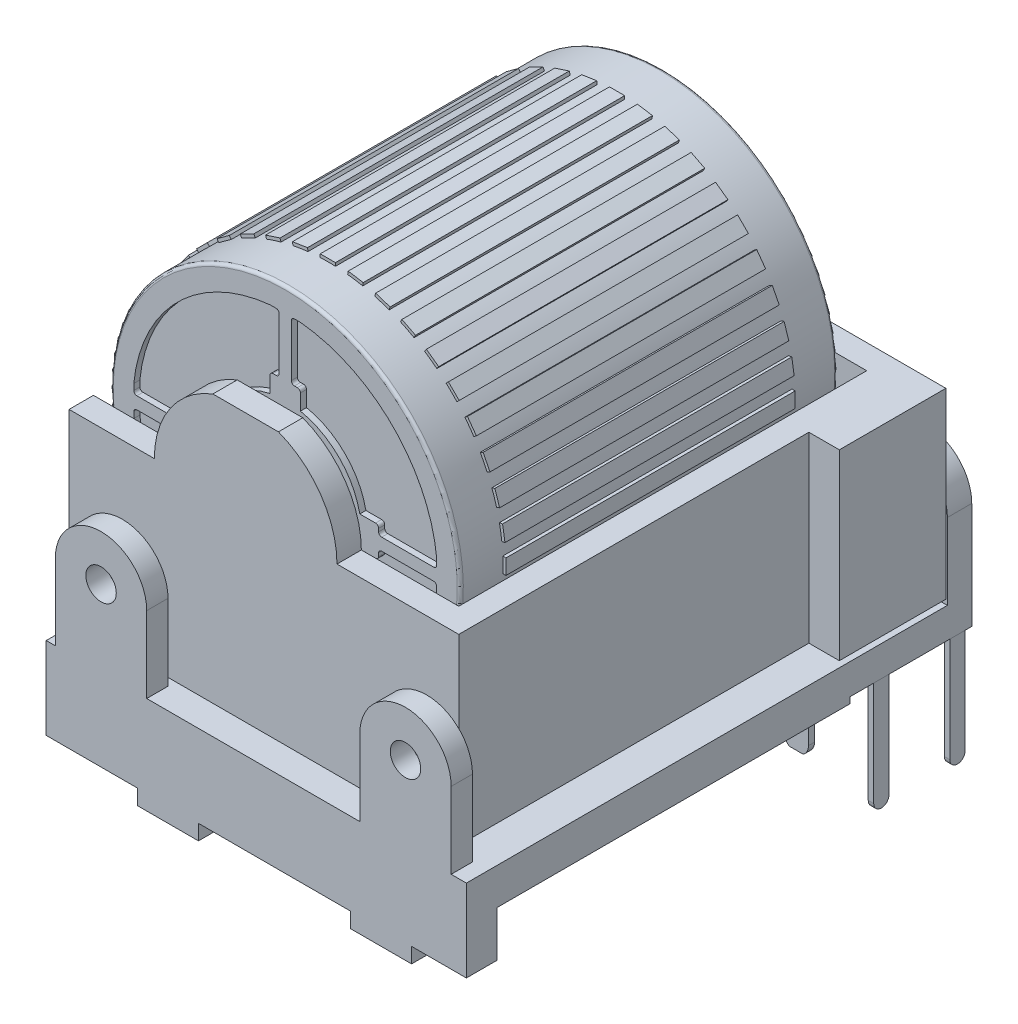
SolidWorks part; units mm, degrees
ref_plane "前视基准面" through (0, 0, 0) normal (0, 0, 1) x (1, 0, 0)
ref_plane "上视基准面" through (0, 0, 0) normal (0, 1, 0) x (1, 0, 0)
ref_plane "右视基准面" through (0, 0, 0) normal (1, 0, 0) x (0, 0, -1)
sketch "草图1" plane through (0, 0, 0) normal (0, 1, 0) x (1, 0, 0)
  line L0 (0, 0) -> (13.8, 0)
  line L1 (13.8, 0) -> (13.8, 16.6)
  line L2 (13.8, 16.6) -> (0, 16.6)
  line L3 (0, 16.6) -> (0, 0)
extrude "凸台-拉伸1" add sketch "草图1" along normal blind 1.2
sketch "草图2" plane through (0, 0, 0) normal (0, -1, 0) x (1, 0, 0)
  line L0 (0, 0) -> (13.8, 0)
  line L1 (13.8, 0) -> (13.8, -1)
  line L2 (13.8, 0) -> (13.8, -16.6) construction
  line L3 (13.8, -1) -> (0, -1)
  line L4 (0, -16.6) -> (0, 0) construction
  line L5 (0, -1) -> (0, 0)
extrude "凸台-拉伸2" add sketch "草图2" along normal blind 1.5
sketch "草图3" plane through (0, -1.5, 0) normal (0, -1, 0) x (1, 0, 0)
  line L1 (13.8, 0) -> (0, 0) construction
  line L2 (12, 0) -> (12, -2.2)
  line L4 (12, -2.2) -> (10, -2.2)
  line L5 (10, -2.2) -> (10, 0)
  line L6 (10, 0) -> (12, 0)
  line L7 (3, 0) -> (3, -2.2)
  line L8 (3, -2.2) -> (5, -2.2)
  line L9 (5, -2.2) -> (5, 0)
  line L10 (5, 0) -> (3, 0)
extrude "凸台-拉伸3" add sketch "草图3" along normal blind 0.5
sketch "草图4" plane through (0, 0, 0) normal (0, 0, 1) x (1, 0, 0)
  line L1 (0, 1.2) -> (13.8, 1.2) construction
  line L2 (0.3, 1.2) -> (0.3, 3.7)
  line L4 (3.3, 3.7) -> (3.3, 1.2)
  line L5 (3.3, 1.2) -> (0.3, 1.2)
  line L7 (13.3, 1.2) -> (13.3, 3.7)
  line L9 (10.3, 3.7) -> (10.3, 1.2)
  line L10 (10.3, 1.2) -> (13.3, 1.2)
  arc A0 (0.3, 3.7) -> (3.3, 3.7) centre (1.8, 3.7) cw
  arc A1 (10.3, 3.7) -> (13.3, 3.7) centre (11.8, 3.7) cw
  circle A2 centre (1.8, 3.7) radius 0.5
  circle A3 centre (11.8, 3.7) radius 0.5
extrude "凸台-拉伸4" add sketch "草图4" against normal blind 0.7
sketch "草图5" plane through (0, 0, -16.6) normal (0, 0, -1) x (-1, 0, 0)
  line L1 (-0.3, 1.2) -> (-3.3, 1.2) construction
  line L2 (-2, 1.2) -> (-2, 3.7)
  line L3 (-3.5, 5.2) -> (-12.3, 5.2)
  line L4 (-13.8, 3.7) -> (-13.8, 1.2)
  line L5 (-13.8, 1.2) -> (-2, 1.2)
  arc A0 (-2, 3.7) -> (-3.5, 5.2) centre (-3.5, 3.7) ccw
  arc A1 (-13.8, 3.7) -> (-12.3, 5.2) centre (-12.3, 3.7) cw
  circle A2 centre (-12.5, 3.7) radius 0.5
  circle A3 centre (-3.3, 3.7) radius 0.5
  dimension "D1" = 1.5
extrude "凸台-拉伸5" add sketch "草图5" against normal blind 0.8
sketch "草图6" plane through (0, 0, 0) normal (0, -1, 0) x (1, 0, 0)
  line L2 (11, -2.7) -> (12.5, -2.7)
  line L3 (12.5, -2.7) -> (12.5, -1)
  line L4 (12, -1) -> (13.8, -1) construction
  line L5 (12.5, -1) -> (9.5, -1)
  line L6 (5, -1) -> (10, -1) construction
  line L7 (9.5, -1) -> (9.5, -2.7)
  line L8 (9.5, -2.7) -> (11, -2.7)
  line L10 (4, -2.7) -> (5.5, -2.7)
  line L11 (5.5, -2.7) -> (5.5, -1)
  line L12 (5.5, -1) -> (2.5, -1)
  line L13 (0, -1) -> (13.8, -1) construction
  line L14 (2.5, -1) -> (2.5, -2.7)
  line L15 (2.5, -2.7) -> (4, -2.7)
extrude "切除-拉伸1" cut sketch "草图6" against normal through all
sketch "草图7" plane through (0, 0, 0) normal (0, -1, 0) x (1, 0, 0)
  line L0 (13.8, -16.6) -> (12.5, -16.6)
  line L2 (13.8, -16.6) -> (0, -16.6) construction
  line L3 (2, -14.8) -> (2, -11.3)
  line L4 (2, -11.3) -> (10, -11.3)
  line L5 (10, -11.3) -> (10, -12.3)
  line L6 (2, -14.8) -> (12, -14.8)
  line L7 (12, -14.8) -> (12, -12.3)
  line L8 (12, -12.3) -> (10, -12.3)
  line L9 (12.5, -16.6) -> (12.5, -12.6)
  line L10 (12.5, -12.6) -> (13.8, -12.6)
  line L11 (13.8, -1) -> (13.8, -16.6) construction
  line L12 (13.8, -12.6) -> (13.8, -16.6)
extrude "切除-拉伸2" cut sketch "草图7" against normal blind 0.2
sketch "草图8" plane through (0, 0.2, 0) normal (0, -1, 0) x (1, 0, 0)
  line L2 (2, -11.3) -> (2, -14.8) construction
  line L3 (2, -13.05) -> (12, -13.05)
  line L4 (12, -14.8) -> (12, -12.3) construction
  line L5 (12, -13.05) -> (12, -12.3)
  line L6 (12, -12.3) -> (10, -12.3) construction
  line L7 (12, -12.3) -> (10, -12.3) construction
  line L8 (12, -12.3) -> (10, -12.3)
  line L9 (10, -12.3) -> (10, -11.3)
  line L10 (10, -11.3) -> (2, -11.3)
  line L11 (2, -11.3) -> (2, -13.05)
extrude "切除-拉伸3" cut sketch "草图8" against normal through all
sketch "草图9" plane through (0, 0.2, 0) normal (0, -1, 0) x (1, 0, 0)
  line L2 (10.81, -14.025) -> (11.21, -14.025)
  line L4 (11.21, -14.025) -> (11.21, -13.825)
  line L6 (13.78, -16.4) -> (13.6, -16.4)
  line L7 (13.6, -16.4) -> (13.6, -15.9)
  line L8 (13.6, -15.9) -> (13.78, -15.9)
  line L9 (11.21, -13.825) -> (10.41, -13.825)
  line L10 (10.41, -13.825) -> (10.41, -14.025)
  line L11 (10.41, -14.025) -> (10.81, -14.025)
  line L13 (8.27, -14.025) -> (8.67, -14.025)
  line L14 (8.67, -14.025) -> (8.67, -13.825)
  line L15 (8.67, -13.825) -> (7.87, -13.825)
  line L16 (7.87, -13.825) -> (7.87, -14.025)
  line L17 (7.87, -14.025) -> (8.27, -14.025)
  line L18 (13.78, -16.4) -> (13.78, -15.9)
  line L19 (5.73, -14.025) -> (6.13, -14.025)
  line L20 (6.13, -14.025) -> (6.13, -13.825)
  line L21 (6.13, -13.825) -> (5.33, -13.825)
  line L22 (5.33, -13.825) -> (5.33, -14.025)
  line L23 (5.33, -14.025) -> (5.73, -14.025)
  line L24 (13.78, -13.9) -> (13.6, -13.9)
  line L25 (3.19, -14.025) -> (3.59, -14.025)
  line L26 (3.59, -14.025) -> (3.59, -13.825)
  line L27 (3.59, -13.825) -> (2.79, -13.825)
  line L28 (2.79, -13.825) -> (2.79, -14.025)
  line L29 (2.79, -14.025) -> (3.19, -14.025)
  line L30 (13.6, -13.9) -> (13.6, -13.4)
  line L31 (13.6, -13.4) -> (13.78, -13.4)
  line L33 (13.78, -13.9) -> (13.78, -13.4)
extrude "凸台-拉伸6" add sketch "草图9" along normal blind 3.7
sketch "草图11" plane through (13.78, 0, 0) normal (1, 0, 0) x (0, 0, -1)
  line L1 (13.9, -3.5) -> (13.4, -3.5) construction
  line L3 (16.4, -3.5) -> (15.9, -3.5) construction
  line L5 (15.9, -3.5) -> (15.9, 0.2) construction
  line L6 (15.9, -3.25) -> (15.9, -3.5)
  line L7 (15.9, -3.5) -> (16.15, -3.5)
  line L8 (16.15, -3.5) -> (16.4, -3.5)
  line L9 (16.4, -3.5) -> (16.4, -3.25)
  line L10 (16.4, -3.5) -> (16.4, 0.2) construction
  line L11 (13.4, -3.25) -> (13.4, -3.5)
  line L12 (13.4, -3.5) -> (13.4, 0.2) construction
  line L13 (13.4, -3.5) -> (13.9, -3.5)
  line L14 (13.9, -3.5) -> (13.9, -3.25)
  line L15 (13.9, -3.5) -> (13.9, 0.2) construction
  arc A0 (13.4, -3.25) -> (13.65, -3.5) centre (13.65, -3.25) ccw
  arc A1 (13.65, -3.5) -> (13.9, -3.25) centre (13.65, -3.25) ccw
  arc A2 (15.9, -3.25) -> (16.4, -3.25) centre (16.15, -3.25) ccw
  line M6 (13.4, 0.2) -> (13.4, -3.5)
  line M7 (13.4, -3.5) -> (13.9, -3.5)
  line M8 (13.9, -3.5) -> (13.9, 0.2)
extrude "切除-拉伸5" cut sketch "草图11" against normal blind 3.7 contours A0 M6 M7 | A1 L13 M8 | A2 L6 L7 | A2 L8 L9
sketch "草图10" plane through (0, 0, -14.025) normal (0, 0, -1) x (-1, 0, 0)
  line L22 (-8.67, -3.5) -> (-8.67, 0.2) construction
  line L23 (-10.41, -3.5) -> (-11.21, -3.5) construction
  line L25 (-7.87, -3.5) -> (-8.67, -3.5) construction
  line L26 (-11.21, -3.5) -> (-11.21, 0.2) construction
  line L27 (-10.41, -3.5) -> (-10.41, 0.2) construction
  line L28 (-11.21, -3.1) -> (-11.21, -3.5)
  line L29 (-11.21, -3.5) -> (-10.81, -3.5)
  line L30 (-10.81, -3.5) -> (-10.41, -3.5)
  line L31 (-10.41, -3.5) -> (-10.41, -3.1)
  line L32 (-7.87, -3.5) -> (-7.87, 0.2) construction
  line L33 (-6.13, -3.5) -> (-6.13, 0.2) construction
  line L34 (-5.33, -3.5) -> (-5.33, 0.2) construction
  line L35 (-3.59, -3.5) -> (-3.59, 0.2) construction
  line L36 (-2.79, -3.5) -> (-2.79, 0.2) construction
  line L37 (-8.67, -3.1) -> (-8.67, -3.5)
  line L38 (-8.67, -3.5) -> (-8.27, -3.5)
  line L39 (-8.27, -3.5) -> (-7.87, -3.5)
  line L40 (-7.87, -3.5) -> (-7.87, -3.1)
  line L41 (-6.13, -3.1) -> (-6.13, -3.5)
  line L42 (-6.13, -3.5) -> (-5.73, -3.5)
  line L43 (-5.73, -3.5) -> (-5.33, -3.5)
  line L44 (-5.33, -3.5) -> (-5.33, -3.1)
  line L45 (-3.59, -3.1) -> (-3.59, -3.5)
  line L46 (-3.59, -3.5) -> (-3.19, -3.5)
  line L47 (-3.19, -3.5) -> (-2.79, -3.5)
  line L48 (-2.79, -3.5) -> (-2.79, -3.1)
  arc A4 (-11.21, -3.1) -> (-10.41, -3.1) centre (-10.81, -3.1) ccw
  arc A5 (-8.67, -3.1) -> (-8.27, -3.5) centre (-8.27, -3.1) ccw
  arc A6 (-8.27, -3.5) -> (-7.87, -3.1) centre (-8.27, -3.1) ccw
  arc A7 (-6.13, -3.1) -> (-5.33, -3.1) centre (-5.73, -3.1) ccw
  arc A8 (-3.59, -3.1) -> (-2.79, -3.1) centre (-3.19, -3.1) ccw
extrude "切除-拉伸4" cut sketch "草图10" against normal blind 3.7 contours A4 L28 L29 | A4 L30 L31 | A7 L43 L44 | A7 L41 L42 | A8 L47 L48 | A8 L45 L46 | L37 L38 A5 | A6 L40 L39
sketch "草图12" plane through (0, 1.2, 0) normal (0, 1, 0) x (1, 0, 0)
  circle A0 centre (6.7271, 7.591) radius 0.5
extrude "凸台-拉伸7" add sketch "草图12" along normal blind 0.2
sketch "草图13" plane through (0, 1.4, 0) normal (0, 1, 0) x (1, 0, 0)
  line L3 (0, 16.6) -> (0, 0) construction
  line L4 (0, 15.75) -> (13.8, 15.75)
  line L5 (13.8, 0) -> (13.8, 15.8) construction
  line L6 (13.8, 15.75) -> (13.8, 12.25)
  line L7 (13.8, 12.25) -> (12.8, 12.25)
  line L8 (12.8, 12.25) -> (12.8, 0.75)
  line L9 (12.8, 0.75) -> (0, 0.75)
  line L10 (0, 0.75) -> (0, 15.75)
extrude "凸台-拉伸8" add sketch "草图13" along normal blind 6
sketch "草图14" plane through (0, 7.4, 0) normal (0, 1, 0) x (1, 0, 0)
  line L1 (0, 15.75) -> (0, 0.75) construction
  line L2 (0, 14.95) -> (0, 1.55)
  line L4 (12, 14.95) -> (0, 14.95)
  line L5 (0, 1.55) -> (12, 1.55)
  line L6 (12, 1.55) -> (12, 14.95)
extrude "切除-拉伸6" cut sketch "草图14" against normal blind 2.8
sketch "草图15" plane through (0, 0, 0) normal (0, -1, 0) x (1, 0, 0)
  circle A0 centre (1, -14.1) radius 0.6
extrude "凸台-拉伸9" add sketch "草图15" along normal blind 1.2
fillet "圆角1" radius 0.1 1 edges at (1, -1.2, -14.7)
sketch "草图16" plane through (0, 0, -15.75) normal (0, 0, -1) x (-1, 0, 0)
  line L0 (-5.8, 7.4) -> (-8.8, 7.4)
  line L1 (-13.8, 7.4) -> (0, 7.4) construction
  line L2 (-2.8, 7.4) -> (-5.8, 7.4)
  line L5 (-6.877, 10.2) -> (-4.723, 10.2)
  arc A0 (-2.8, 7.4) -> (-4.723, 10.2) centre (-5.8, 7.4) ccw
  arc A1 (-6.877, 10.2) -> (-8.8, 7.4) centre (-5.8, 7.4) ccw
extrude "凸台-拉伸10" add sketch "草图16" against normal blind 0.8
sketch "草图17" plane through (0, 0, -0.75) normal (0, 0, 1) x (1, 0, 0)
  line L0 (0, 7.4) -> (12.8, 7.4) construction
  line L1 (2.8, 7.4) -> (8.8, 7.4)
  line L2 (6.877, 10.2) -> (4.723, 10.2)
  arc A0 (2.8, 7.4) -> (4.723, 10.2) centre (5.8, 7.4) cw
  arc A1 (6.877, 10.2) -> (8.8, 7.4) centre (5.8, 7.4) cw
extrude "凸台-拉伸11" add sketch "草图17" against normal blind 0.8
sketch "草图18" plane through (0, 0, -14.95) normal (0, 0, 1) x (1, 0, 0)
  circle A0 centre (5.8, 7.4) radius 2
extrude "凸台-拉伸12" add sketch "草图18" along normal blind 0.5
sketch "草图19" plane through (0, 0, -1.55) normal (0, 0, -1) x (-1, 0, 0)
  circle A0 centre (-5.8, 7.4) radius 2
extrude "凸台-拉伸13" add sketch "草图19" along normal blind 0.5
sketch "草图20" plane through (0, 0, -2.05) normal (0, 0, -1) x (-1, 0, 0)
  circle A0 centre (-5.8, 7.4) radius 5.75
extrude "凸台-拉伸14" add sketch "草图20" along normal blind 12.4
fillet "圆角2" radius 0.1 1 edges at (5.8, 13.15, -14.45)
fillet "圆角3" radius 0.1 1 edges at (5.8, 13.15, -2.05)
sketch "草图21" plane through (0, 0, -14.45) normal (0, 0, -1) x (-1, 0, 0)
  circle A0 centre (-5.8, 7.4) radius 4.85
  circle A1 centre (-5.8, 7.4) radius 4
extrude "凸台-拉伸15" add sketch "草图21" along normal blind 0.1
sketch "草图22" plane through (0, 0, -14.45) normal (0, 0, -1) x (-1, 0, 0)
  circle A0 centre (-5.8, 7.4) radius 4
extrude "凸台-拉伸16" add sketch "草图22" along normal blind 0.2
sketch "草图23" plane through (0, 0, -2.05) normal (0, 0, 1) x (1, 0, 0)
  line L0 (5.4006, 10.4674) -> (5.5, 10.4674)
  line L1 (6.1, 10.4674) -> (6.1994, 10.4674)
  line L2 (5.3006, 10.3674) -> (5.3006, 9.8496)
  line L4 (6.2994, 9.8496) -> (6.2994, 10.3674)
  line L5 (0.925, 7.2) -> (2.6326, 7.2)
  line L6 (5.5, 12.375) -> (5.3006, 12.375)
  line L7 (2.7326, 7.0006) -> (2.7326, 7.1)
  line L8 (6.1, 12.375) -> (6.2994, 12.375)
  line L9 (5.6, 12.275) -> (5.6, 10.5674)
  line L10 (6, 12.275) -> (6, 10.5674)
  line L11 (2.8326, 6.9006) -> (3.3504, 6.9006)
  line L12 (0.925, 7.6) -> (2.6326, 7.6)
  line L13 (3.3504, 7.8994) -> (2.8326, 7.8994)
  line L14 (0.825, 7.1) -> (0.825, 6.9006)
  line L15 (2.7326, 7.7) -> (2.7326, 7.7994)
  line L16 (0.825, 7.7) -> (0.825, 7.8994)
  line L17 (10.675, 7.6) -> (8.9674, 7.6)
  line L18 (8.8674, 7.7994) -> (8.8674, 7.7)
  line L19 (8.7674, 7.8994) -> (8.2496, 7.8994)
  line L20 (10.675, 7.2) -> (8.9674, 7.2)
  line L21 (8.2496, 6.9006) -> (8.7674, 6.9006)
  line L22 (10.775, 7.7) -> (10.775, 7.8994)
  line L23 (8.8674, 7.1) -> (8.8674, 7.0006)
  line L24 (10.775, 7.1) -> (10.775, 6.9006)
  arc A0 (5.3006, 12.375) -> (0.825, 7.8994) centre (5.8, 7.4) ccw
  arc A1 (5.3006, 9.8496) -> (3.3504, 7.8994) centre (5.8, 7.4) ccw
  arc A2 (6.2994, 10.3674) -> (6.1994, 10.4674) centre (6.1994, 10.3674) ccw
  arc A3 (6.1, 10.4674) -> (6, 10.5674) centre (6.1, 10.5674) cw
  arc A4 (5.6, 10.5674) -> (5.5, 10.4674) centre (5.5, 10.5674) cw
  arc A5 (5.3006, 10.3674) -> (5.4006, 10.4674) centre (5.4006, 10.3674) cw
  arc A6 (6, 12.275) -> (6.1, 12.375) centre (6.1, 12.275) cw
  arc A7 (5.6, 12.275) -> (5.5, 12.375) centre (5.5, 12.275) ccw
  arc A8 (2.8326, 6.9006) -> (2.7326, 7.0006) centre (2.8326, 7.0006) cw
  arc A9 (0.925, 7.2) -> (0.825, 7.1) centre (0.925, 7.1) ccw
  arc A10 (0.925, 7.6) -> (0.825, 7.7) centre (0.925, 7.7) cw
  arc A11 (2.6326, 7.2) -> (2.7326, 7.1) centre (2.6326, 7.1) cw
  arc A12 (2.8326, 7.8994) -> (2.7326, 7.7994) centre (2.8326, 7.7994) ccw
  arc A13 (2.7326, 7.7) -> (2.6326, 7.6) centre (2.6326, 7.7) cw
  arc A14 (8.7674, 7.8994) -> (8.8674, 7.7994) centre (8.7674, 7.7994) cw
  arc A15 (10.675, 7.6) -> (10.775, 7.7) centre (10.675, 7.7) ccw
  arc A16 (10.675, 7.2) -> (10.775, 7.1) centre (10.675, 7.1) cw
  arc A17 (8.9674, 7.6) -> (8.8674, 7.7) centre (8.9674, 7.7) cw
  arc A18 (8.7674, 6.9006) -> (8.8674, 7.0006) centre (8.7674, 7.0006) ccw
  arc A19 (8.8674, 7.1) -> (8.9674, 7.2) centre (8.9674, 7.1) cw
  arc A20 (0.825, 6.9006) -> (10.775, 6.9006) centre (5.8, 7.4) ccw
  arc A21 (3.3504, 6.9006) -> (8.2496, 6.9006) centre (5.8, 7.4) ccw
  arc A22 (8.2496, 7.8994) -> (6.2994, 9.8496) centre (5.8, 7.4) ccw
  arc A23 (10.775, 7.8994) -> (6.2994, 12.375) centre (5.8, 7.4) ccw
  point P17 (6, 10.4674)
  dimension "D1" = 0.1
  dimension "D2" = 0.1
  dimension "D3" = 0.1
extrude "切除-拉伸7" cut sketch "草图23" against normal blind 0.2
ref_plane "基准面1" through (0, 0, -12.95) normal (0, 0, -1) x (-1, 0, 0)
sketch "草图24" plane through (0, 0, -12.95) normal (0, 0, -1) x (-1, 0, 0)
  line L1 (-4.6544, 13.0347) -> (-5.1483, 13.1129)
  line L2 (-5.8, 13.25) -> (-6.05, 13.25)
  line L3 (-6.05, 13.25) -> (-6.05, 13.1446)
  line L4 (-5.8, 13.25) -> (-5.55, 13.25)
  line L5 (-5.55, 13.25) -> (-5.55, 13.1446)
  line L6 (-5.55, 13.1446) -> (-6.05, 13.1446)
  line L7 (-4.6379, 13.1389) -> (-4.6544, 13.0347)
  line L8 (-4.8849, 13.178) -> (-4.6379, 13.1389)
  line L9 (-4.8849, 13.178) -> (-5.1318, 13.2171)
  line L10 (-5.1318, 13.2171) -> (-5.1483, 13.1129)
  line L11 (-3.7871, 12.7861) -> (-4.2626, 12.9407)
  line L12 (-3.7545, 12.8864) -> (-3.7871, 12.7861)
  line L13 (-3.9923, 12.9637) -> (-3.7545, 12.8864)
  line L14 (-3.9923, 12.9637) -> (-4.23, 13.0409)
  line L15 (-4.23, 13.0409) -> (-4.2626, 12.9407)
  line L16 (-2.9693, 12.4049) -> (-3.4148, 12.6319)
  line L17 (-2.9214, 12.4989) -> (-2.9693, 12.4049)
  line L18 (-3.1442, 12.6124) -> (-2.9214, 12.4989)
  line L19 (-3.1442, 12.6124) -> (-3.3669, 12.7259)
  line L20 (-3.3669, 12.7259) -> (-3.4148, 12.6319)
  line L21 (-2.2212, 11.9005) -> (-2.6257, 12.1944)
  line L22 (-2.1592, 11.9858) -> (-2.2212, 11.9005)
  line L23 (-2.3615, 12.1327) -> (-2.1592, 11.9858)
  line L24 (-2.3615, 12.1327) -> (-2.5637, 12.2797)
  line L25 (-2.5637, 12.2797) -> (-2.6257, 12.1944)
  line L26 (-1.5612, 11.2852) -> (-1.9148, 11.6388)
  line L27 (-1.4866, 11.3598) -> (-1.5612, 11.2852)
  line L28 (-1.6634, 11.5366) -> (-1.4866, 11.3598)
  line L29 (-1.6634, 11.5366) -> (-1.8402, 11.7134)
  line L30 (-1.8402, 11.7134) -> (-1.9148, 11.6388)
  line L31 (-1.0056, 10.5743) -> (-1.2995, 10.9788)
  line L32 (-0.9203, 10.6363) -> (-1.0056, 10.5743)
  line L33 (-1.0673, 10.8385) -> (-0.9203, 10.6363)
  line L34 (-1.0673, 10.8385) -> (-1.2142, 11.0408)
  line L35 (-1.2142, 11.0408) -> (-1.2995, 10.9788)
  line L36 (-0.5681, 9.7852) -> (-0.7951, 10.2307)
  line L37 (-0.4741, 9.8331) -> (-0.5681, 9.7852)
  line L38 (-0.5876, 10.0558) -> (-0.4741, 9.8331)
  line L39 (-0.5876, 10.0558) -> (-0.7011, 10.2786)
  line L40 (-0.7011, 10.2786) -> (-0.7951, 10.2307)
  line L41 (-0.2593, 8.9374) -> (-0.4139, 9.4129)
  line L42 (-0.1591, 8.97) -> (-0.2593, 8.9374)
  line L43 (-0.2363, 9.2077) -> (-0.1591, 8.97)
  line L44 (-0.2363, 9.2077) -> (-0.3136, 9.4455)
  line L45 (-0.3136, 9.4455) -> (-0.4139, 9.4129)
  line L46 (-0.0871, 8.0517) -> (-0.1653, 8.5456)
  line L47 (0.0171, 8.0682) -> (-0.0871, 8.0517)
  line L48 (-0.022, 8.3151) -> (0.0171, 8.0682)
  line L49 (-0.022, 8.3151) -> (-0.0611, 8.5621)
  line L50 (-0.0611, 8.5621) -> (-0.1653, 8.5456)
  line L51 (-0.0554, 7.15) -> (-0.0554, 7.65)
  line L52 (0.05, 7.15) -> (-0.0554, 7.15)
  line L53 (0.05, 7.4) -> (0.05, 7.15)
  line L54 (0.05, 7.4) -> (0.05, 7.65)
  line L55 (0.05, 7.65) -> (-0.0554, 7.65)
  line L56 (-0.1653, 6.2544) -> (-0.0871, 6.7483)
  line L57 (-0.0611, 6.2379) -> (-0.1653, 6.2544)
  line L58 (-0.022, 6.4849) -> (-0.0611, 6.2379)
  line L59 (-0.022, 6.4849) -> (0.0171, 6.7318)
  line L60 (0.0171, 6.7318) -> (-0.0871, 6.7483)
  line L61 (-0.4139, 5.3871) -> (-0.2593, 5.8626)
  line L62 (-0.3136, 5.3545) -> (-0.4139, 5.3871)
  line L63 (-0.2363, 5.5923) -> (-0.3136, 5.3545)
  line L64 (-0.2363, 5.5923) -> (-0.1591, 5.83)
  line L65 (-0.1591, 5.83) -> (-0.2593, 5.8626)
  line L66 (-0.7951, 4.5693) -> (-0.5681, 5.0148)
  line L67 (-0.7011, 4.5214) -> (-0.7951, 4.5693)
  line L68 (-0.5876, 4.7442) -> (-0.7011, 4.5214)
  line L69 (-0.5876, 4.7442) -> (-0.4741, 4.9669)
  line L70 (-0.4741, 4.9669) -> (-0.5681, 5.0148)
  line L71 (-1.2995, 3.8212) -> (-1.0056, 4.2257)
  line L72 (-1.2142, 3.7592) -> (-1.2995, 3.8212)
  line L73 (-1.0673, 3.9615) -> (-1.2142, 3.7592)
  line L74 (-1.0673, 3.9615) -> (-0.9203, 4.1637)
  line L75 (-0.9203, 4.1637) -> (-1.0056, 4.2257)
  line L76 (-1.9148, 3.1612) -> (-1.5612, 3.5148)
  line L77 (-1.8402, 3.0866) -> (-1.9148, 3.1612)
  line L78 (-1.6634, 3.2634) -> (-1.8402, 3.0866)
  line L79 (-1.6634, 3.2634) -> (-1.4866, 3.4402)
  line L80 (-1.4866, 3.4402) -> (-1.5612, 3.5148)
  line L81 (-2.6257, 2.6056) -> (-2.2212, 2.8995)
  line L82 (-2.5637, 2.5203) -> (-2.6257, 2.6056)
  line L83 (-2.3615, 2.6673) -> (-2.5637, 2.5203)
  line L84 (-2.3615, 2.6673) -> (-2.1592, 2.8142)
  line L85 (-2.1592, 2.8142) -> (-2.2212, 2.8995)
  line L86 (-3.4148, 2.1681) -> (-2.9693, 2.3951)
  line L87 (-3.3669, 2.0741) -> (-3.4148, 2.1681)
  line L88 (-3.1442, 2.1876) -> (-3.3669, 2.0741)
  line L89 (-3.1442, 2.1876) -> (-2.9214, 2.3011)
  line L90 (-2.9214, 2.3011) -> (-2.9693, 2.3951)
  line L91 (-4.2626, 1.8593) -> (-3.7871, 2.0139)
  line L92 (-4.23, 1.7591) -> (-4.2626, 1.8593)
  line L93 (-3.9923, 1.8363) -> (-4.23, 1.7591)
  line L94 (-3.9923, 1.8363) -> (-3.7545, 1.9136)
  line L95 (-3.7545, 1.9136) -> (-3.7871, 2.0139)
  line L96 (-5.1483, 1.6871) -> (-4.6544, 1.7653)
  line L97 (-5.1318, 1.5829) -> (-5.1483, 1.6871)
  line L98 (-4.8849, 1.622) -> (-5.1318, 1.5829)
  line L99 (-4.8849, 1.622) -> (-4.6379, 1.6611)
  line L100 (-4.6379, 1.6611) -> (-4.6544, 1.7653)
  line L101 (-6.05, 1.6554) -> (-5.55, 1.6554)
  line L102 (-6.05, 1.55) -> (-6.05, 1.6554)
  line L103 (-5.8, 1.55) -> (-6.05, 1.55)
  line L104 (-5.8, 1.55) -> (-5.55, 1.55)
  line L105 (-5.55, 1.55) -> (-5.55, 1.6554)
  line L106 (-6.9456, 1.7653) -> (-6.4517, 1.6871)
  line L107 (-6.9621, 1.6611) -> (-6.9456, 1.7653)
  line L108 (-6.7151, 1.622) -> (-6.9621, 1.6611)
  line L109 (-6.7151, 1.622) -> (-6.4682, 1.5829)
  line L110 (-6.4682, 1.5829) -> (-6.4517, 1.6871)
  line L111 (-7.8129, 2.0139) -> (-7.3374, 1.8593)
  line L112 (-7.8455, 1.9136) -> (-7.8129, 2.0139)
  line L113 (-7.6077, 1.8363) -> (-7.8455, 1.9136)
  line L114 (-7.6077, 1.8363) -> (-7.37, 1.7591)
  line L115 (-7.37, 1.7591) -> (-7.3374, 1.8593)
  line L116 (-8.6307, 2.3951) -> (-8.1852, 2.1681)
  line L117 (-8.6786, 2.3011) -> (-8.6307, 2.3951)
  line L118 (-8.4558, 2.1876) -> (-8.6786, 2.3011)
  line L119 (-8.4558, 2.1876) -> (-8.2331, 2.0741)
  line L120 (-8.2331, 2.0741) -> (-8.1852, 2.1681)
  line L121 (-9.3788, 2.8995) -> (-8.9743, 2.6056)
  line L122 (-9.4408, 2.8142) -> (-9.3788, 2.8995)
  line L123 (-9.2385, 2.6673) -> (-9.4408, 2.8142)
  line L124 (-9.2385, 2.6673) -> (-9.0363, 2.5203)
  line L125 (-9.0363, 2.5203) -> (-8.9743, 2.6056)
  line L126 (-10.0388, 3.5148) -> (-9.6852, 3.1612)
  line L127 (-10.1134, 3.4402) -> (-10.0388, 3.5148)
  line L128 (-9.9366, 3.2634) -> (-10.1134, 3.4402)
  line L129 (-9.9366, 3.2634) -> (-9.7598, 3.0866)
  line L130 (-9.7598, 3.0866) -> (-9.6852, 3.1612)
  line L131 (-10.5944, 4.2257) -> (-10.3005, 3.8212)
  line L132 (-10.6797, 4.1637) -> (-10.5944, 4.2257)
  line L133 (-10.5327, 3.9615) -> (-10.6797, 4.1637)
  line L134 (-10.5327, 3.9615) -> (-10.3858, 3.7592)
  line L135 (-10.3858, 3.7592) -> (-10.3005, 3.8212)
  line L136 (-11.0319, 5.0148) -> (-10.8049, 4.5693)
  line L137 (-11.1259, 4.9669) -> (-11.0319, 5.0148)
  line L138 (-11.0124, 4.7442) -> (-11.1259, 4.9669)
  line L139 (-11.0124, 4.7442) -> (-10.8989, 4.5214)
  line L140 (-10.8989, 4.5214) -> (-10.8049, 4.5693)
  line L141 (-11.3407, 5.8626) -> (-11.1861, 5.3871)
  line L142 (-11.4409, 5.83) -> (-11.3407, 5.8626)
  line L143 (-11.3637, 5.5923) -> (-11.4409, 5.83)
  line L144 (-11.3637, 5.5923) -> (-11.2864, 5.3545)
  line L145 (-11.2864, 5.3545) -> (-11.1861, 5.3871)
  line L146 (-11.5129, 6.7483) -> (-11.4347, 6.2544)
  line L147 (-11.6171, 6.7318) -> (-11.5129, 6.7483)
  line L148 (-11.578, 6.4849) -> (-11.6171, 6.7318)
  line L149 (-11.578, 6.4849) -> (-11.5389, 6.2379)
  line L150 (-11.5389, 6.2379) -> (-11.4347, 6.2544)
  line L151 (-11.5446, 7.65) -> (-11.5446, 7.15)
  line L152 (-11.65, 7.65) -> (-11.5446, 7.65)
  line L153 (-11.65, 7.4) -> (-11.65, 7.65)
  line L154 (-11.65, 7.4) -> (-11.65, 7.15)
  line L155 (-11.65, 7.15) -> (-11.5446, 7.15)
  line L156 (-11.4347, 8.5456) -> (-11.5129, 8.0517)
  line L157 (-11.5389, 8.5621) -> (-11.4347, 8.5456)
  line L158 (-11.578, 8.3151) -> (-11.5389, 8.5621)
  line L159 (-11.578, 8.3151) -> (-11.6171, 8.0682)
  line L160 (-11.6171, 8.0682) -> (-11.5129, 8.0517)
  line L161 (-11.1861, 9.4129) -> (-11.3407, 8.9374)
  line L162 (-11.2864, 9.4455) -> (-11.1861, 9.4129)
  line L163 (-11.3637, 9.2077) -> (-11.2864, 9.4455)
  line L164 (-11.3637, 9.2077) -> (-11.4409, 8.97)
  line L165 (-11.4409, 8.97) -> (-11.3407, 8.9374)
  line L166 (-10.8049, 10.2307) -> (-11.0319, 9.7852)
  line L167 (-10.8989, 10.2786) -> (-10.8049, 10.2307)
  line L168 (-11.0124, 10.0558) -> (-10.8989, 10.2786)
  line L169 (-11.0124, 10.0558) -> (-11.1259, 9.8331)
  line L170 (-11.1259, 9.8331) -> (-11.0319, 9.7852)
  line L171 (-10.3005, 10.9788) -> (-10.5944, 10.5743)
  line L172 (-10.3858, 11.0408) -> (-10.3005, 10.9788)
  line L173 (-10.5327, 10.8385) -> (-10.3858, 11.0408)
  line L174 (-10.5327, 10.8385) -> (-10.6797, 10.6363)
  line L175 (-10.6797, 10.6363) -> (-10.5944, 10.5743)
  line L176 (-9.6852, 11.6388) -> (-10.0388, 11.2852)
  line L177 (-9.7598, 11.7134) -> (-9.6852, 11.6388)
  line L178 (-9.9366, 11.5366) -> (-9.7598, 11.7134)
  line L179 (-9.9366, 11.5366) -> (-10.1134, 11.3598)
  line L180 (-10.1134, 11.3598) -> (-10.0388, 11.2852)
  line L181 (-8.9743, 12.1944) -> (-9.3788, 11.9005)
  line L182 (-9.0363, 12.2797) -> (-8.9743, 12.1944)
  line L183 (-9.2385, 12.1327) -> (-9.0363, 12.2797)
  line L184 (-9.2385, 12.1327) -> (-9.4408, 11.9858)
  line L185 (-9.4408, 11.9858) -> (-9.3788, 11.9005)
  line L186 (-8.1852, 12.6319) -> (-8.6307, 12.4049)
  line L187 (-8.2331, 12.7259) -> (-8.1852, 12.6319)
  line L188 (-8.4558, 12.6124) -> (-8.2331, 12.7259)
  line L189 (-8.4558, 12.6124) -> (-8.6786, 12.4989)
  line L190 (-8.6786, 12.4989) -> (-8.6307, 12.4049)
  line L191 (-7.3374, 12.9407) -> (-7.8129, 12.7861)
  line L192 (-7.37, 13.0409) -> (-7.3374, 12.9407)
  line L193 (-7.6077, 12.9637) -> (-7.37, 13.0409)
  line L194 (-7.6077, 12.9637) -> (-7.8455, 12.8864)
  line L195 (-7.8455, 12.8864) -> (-7.8129, 12.7861)
  line L196 (-6.4517, 13.1129) -> (-6.9456, 13.0347)
  line L197 (-6.4682, 13.2171) -> (-6.4517, 13.1129)
  line L198 (-6.7151, 13.178) -> (-6.4682, 13.2171)
  line L199 (-6.7151, 13.178) -> (-6.9621, 13.1389)
  line L200 (-6.9621, 13.1389) -> (-6.9456, 13.0347)
  arc A0 (-0.7778, 4.6) -> (-10.8222, 4.6) centre (-5.8, 7.4) ccw construction
  point P208 (-5.8, 7.4)
  dimension "D1" = 40
extrude "凸台-拉伸17" add sketch "草图24" against normal blind 9.5
